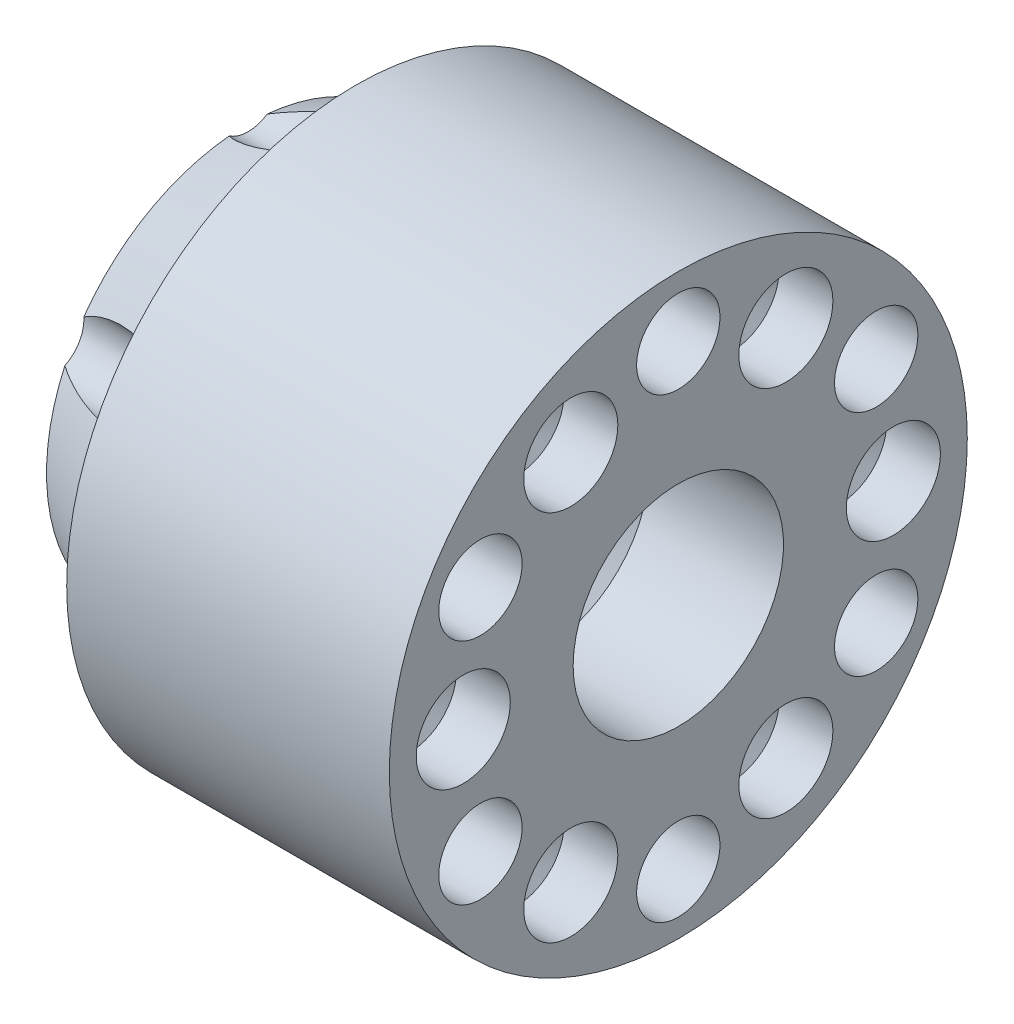
SolidWorks part; units mm, degrees
material "2018 Alloy"
ref_plane "Front Plane" through (0, 0, 0) normal (0, 0, 1) x (1, 0, 0)
ref_plane "Top Plane" through (0, 0, 0) normal (0, 1, 0) x (1, 0, 0)
ref_plane "Right Plane" through (0, 0, 0) normal (1, 0, 0) x (0, 0, -1)
sketch "Sketch1" plane through (0, 0, 0) normal (0, 0, 1) x (1, 0, 0)
  line L2 (8, 18.5) -> (0, 15)
  line L4 (0, 8.5675) -> (0, 0) construction
  line L5 (32, 0) -> (32, 7.825) construction
  line L7 (0, 0) -> (32, 0) construction
  line L13 (32, 7.825) -> (22, 7.825)
  line L14 (22, 7.825) -> (20.675, 6.5)
  line L15 (20.675, 6.5) -> (0, 8.5675)
  line L16 (8, 18.5) -> (8, 21.5)
  line L17 (8, 21.5) -> (32, 21.5)
  line L18 (0, 15) -> (0, 8.5675)
  line L26 (32, 21.5) -> (32, 7.825)
  line L27 (20.675, 6.5) -> (10.675, 6.5) construction
  line L28 (10.675, 6.5) -> (10.675, 7.5) construction
  dimension "D4" = 32
  dimension "D5" = 24
  dimension "D6" = 10
  dimension "D8" = 15.65
  dimension "D9" = 45
  dimension "D10" = 13
  dimension "D13" = 8
  dimension "D14" = 37
  dimension "D15" = 30
  dimension "D16" = 43
  dimension "D17" = 66.371
  dimension "D19" = 20.675
  dimension "D20" = 10
  dimension "D27" = 1
  dimension "D28" = 5.711
  dimension "D29" = 17.135
  dimension "D31" = 1.325
revolve "Revolve1" add sketch "Sketch1" angle 360 about L7
sketch "Sketch11" plane through (32, 0, 0) normal (1, 0, 0) x (0, 0, -1)
  line L0 (0, 0) -> (0, -17) construction
  circle A0 centre (0, 0) radius 17 construction
  circle A1 centre (0, -17) radius 3.1
  circle A2 centre (-14.7224, -8.5) radius 3.1
  circle A3 centre (-14.7224, 8.5) radius 3.1
  circle A4 centre (0, 17) radius 3.1
  circle A5 centre (14.7224, 8.5) radius 3.1
  circle A6 centre (14.7224, -8.5) radius 3.1
  dimension "D1" = 34
  dimension "D2" = 6.2
extrude "Extrude1" cut sketch "Sketch11" against normal blind 12
sketch "Sketch12" plane through (20, 0, 0) normal (1, 0, 0) x (0, 0, -1)
  circle A0 centre (0, -17) radius 3
  circle A1 centre (-14.7224, -8.5) radius 3
  circle A2 centre (-14.7224, 8.5) radius 3
  circle A3 centre (0, 17) radius 3
  circle A4 centre (14.7224, 8.5) radius 3
  circle A5 centre (14.7224, -8.5) radius 3
  dimension "D1" = 6
hole_wizard "M6 Tapped Hole1" positions "3DSketch1" profile "Sketch13" tap size "M6" standard "DIN"
sketch3d "3DSketch1"
  point P0 (20, -17, 0)
  point P3 (20, -8.5, 14.7224)
  point P6 (20, 8.5, 14.7224)
  point P9 (20, 17, 0)
  point P12 (20, 8.5, -14.7224)
  point P15 (20, -8.5, -14.7224)
sketch "Sketch13" plane through (20, -17, 0) normal (0, 1, 0) x (0, 0, -1)
  line L0 (0, 0) -> (0, 36.5022)
  line L1 (0, 36.5022) -> (2.5, 35)
  line L2 (2.5, 35) -> (2.5, 0)
  line L5 (2.5, 0) -> (0, 0)
  line L10 (0, 36.5022) -> (-2.5, 35) construction
  line L11 (0, -6.35) -> (0, 107.95) construction
  dimension "Tap Drill Dia." = 5
  dimension "Tap Drill Depth" = 35
  dimension "Drill Angle" = 118
cosmetic thread "Hole Thread3"
cosmetic thread "Hole Thread4"
cosmetic thread "Hole Thread5"
cosmetic thread "Hole Thread6"
cosmetic thread "Hole Thread7"
cosmetic thread "Hole Thread8"
sketch "Sketch14" plane through (32, 0, 0) normal (1, 0, 0) x (0, 0, -1)
  line L0 (0, -16) -> (0, 0) construction
  line L1 (0, 0) -> (8, -13.8564) construction
  circle A0 centre (0, 0) radius 16 construction
  circle A1 centre (8, -13.8564) radius 3.5
  circle A2 centre (-8, -13.8564) radius 3.5
  circle A3 centre (-16, 0) radius 3.5
  circle A4 centre (-8, 13.8564) radius 3.5
  circle A5 centre (8, 13.8564) radius 3.5
  circle A6 centre (16, 0) radius 3.5
  dimension "D1" = 32
  dimension "D3" = 7
  dimension "D2" = 30
hole_wizard "Ø7.0 (7) Diameter Hole1" positions "3DSketch2" profile "Sketch15" hole size "Ø7.0" standard "DIN"
sketch3d "3DSketch2"
  point P0 (32, -13.8564, -8)
  point P3 (32, -13.8564, 8)
  point P6 (32, 0, 16)
  point P9 (32, 13.8564, 8)
  point P12 (32, 13.8564, -8)
  point P15 (32, 0, -16)
sketch "Sketch15" plane through (32, -13.8564, -8) normal (0, 1, 0) x (0, 0, -1)
  line L0 (0, 0) -> (0, 6.103)
  line L1 (0, 6.103) -> (3.5, 4)
  line L2 (3.5, 4) -> (3.5, 0)
  line L5 (3.5, 0) -> (0, 0)
  line L10 (0, 6.103) -> (-3.5, 4) construction
  line L11 (0, -6.35) -> (0, 107.95) construction
  dimension "Hole Dia." = 7
  dimension "Hole Depth" = 4
  dimension "Drill Angle" = 118
sketch "Sketch17" plane through (0, 0, 0) normal (0, 0, 1) x (1, 0, 0)
  line L0 (0, 0) -> (0, 33.2506)
sketch "Sketch18" plane through (0, 0, 0) normal (0, 0, 1) x (1, 0, 0)
  line L0 (23.5706, 5.306) -> (-1.0846, 7.7715)
  line L1 (-1.0846, 7.7715) -> (-0.7861, 10.7566)
  line L2 (-0.7861, 10.7566) -> (23.8691, 8.2911)
  line L3 (23.8691, 8.2911) -> (23.5706, 5.306)
  line L4 (20.675, 6.5) -> (0, 8.5675) construction
  dimension "D1" = 2.1
  dimension "D2" = 3
  dimension "D3" = 1
  dimension "D4" = 3
extrude "Extrude3" cut sketch "Sketch18" against normal mid plane 2
